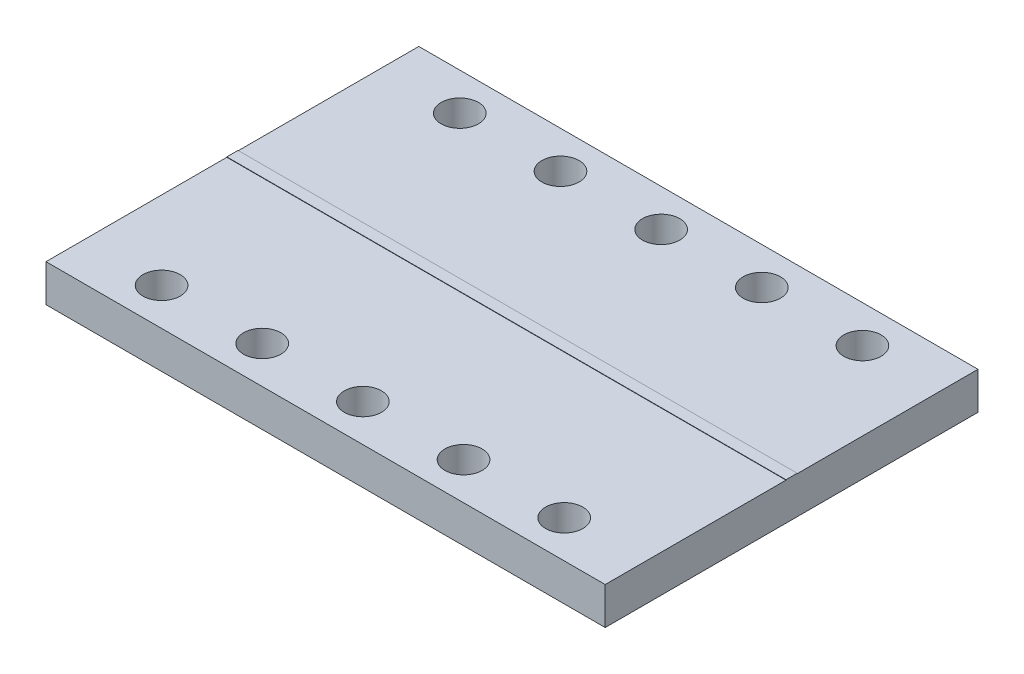
SolidWorks part; units mm, degrees
ref_plane "Front Plane" through (0, 0, 0) normal (0, 0, 1) x (1, 0, 0)
ref_plane "Top Plane" through (0, 0, 0) normal (0, 1, 0) x (1, 0, 0)
ref_plane "Right Plane" through (0, 0, 0) normal (1, 0, 0) x (0, 0, -1)
sketch "Sketch1" plane through (0, 0, 0) normal (0, 1, 0) x (1, 0, 0)
  line L0 (-750, -500) -> (-750, -400) construction
  line L1 (-750, -500) -> (750, -500)
  line L2 (-750, -500) -> (-750, 500)
  line L3 (-750, 500) -> (750, 500)
  line L4 (750, -500) -> (750, 500)
  line L5 (-750, -500) -> (750, 500) construction
  line L6 (-750, 500) -> (750, -500) construction
  line L7 (-750, -400) -> (-540, -400) construction
  circle A0 centre (-540, -400) radius 50
  circle A1 centre (-270, -400) radius 50
  circle A2 centre (0, -400) radius 50
  circle A3 centre (270, -400) radius 50
  circle A4 centre (540, -400) radius 50
  circle A5 centre (-270, 400) radius 50
  circle A6 centre (0, 400) radius 50
  circle A7 centre (270, 400) radius 50
  circle A8 centre (540, 400) radius 50
  circle A9 centre (-540, 400) radius 50
  point P0 (0, 0)
  dimension "D5" = 100
  dimension "D9" = 210
  dimension "D1" = 1500
  dimension "D2" = 1000
  dimension "D3" = 100
  dimension "D4" = 210
  dimension "D8" = 800
  dimension "D10" = 270
  dimension "D6" = 5
  dimension "D7" = 2
extrude "Boss-Extrude1" add sketch "Sketch1" along normal blind 100
sketch "Sketch2" plane through (0, 100, 0) normal (0, 1, 0) x (1, 0, 0)
  line L0 (-750, 0) -> (-750, 15)
  line L1 (-750, 500) -> (-750, -500) construction
  line L2 (-750, 15) -> (750, 15)
  line L3 (750, -500) -> (750, 500) construction
  line L4 (750, 15) -> (750, -15)
  line L5 (750, -15) -> (-750, -15)
  line L6 (-750, -15) -> (-750, 0)
  dimension "D1" = 15
  dimension "D2" = 15
extrude "Boss-Extrude2" add sketch "Sketch2" along normal blind 1
